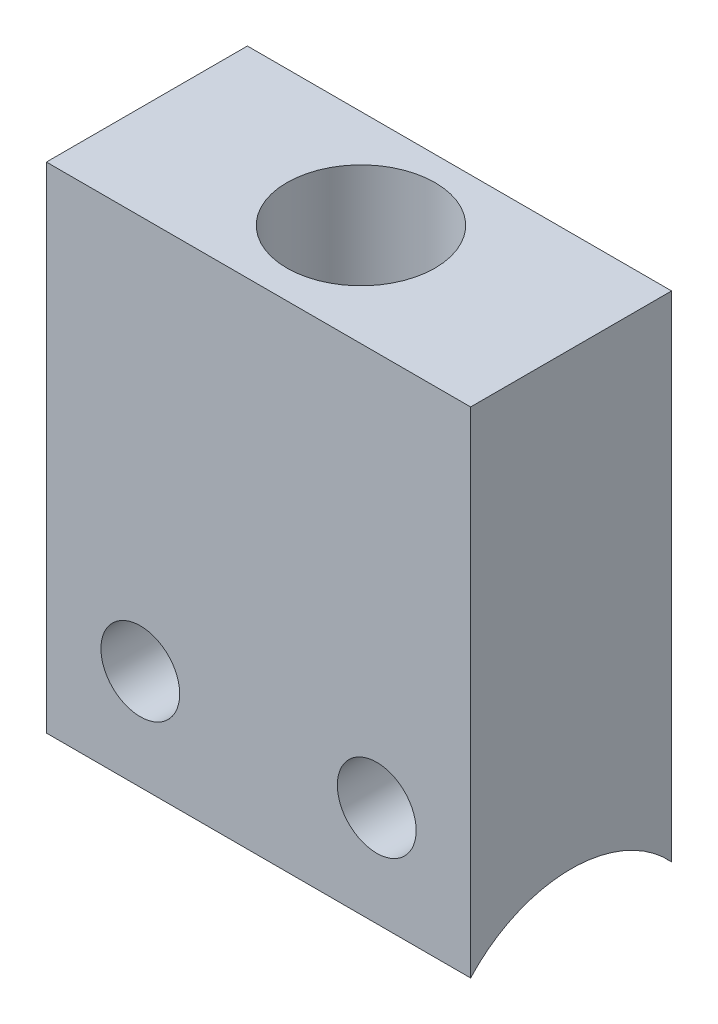
SolidWorks part; units mm, degrees
ref_plane "Front" through (0, 0, 0) normal (0, 0, 1) x (1, 0, 0)
ref_plane "Top" through (0, 0, 0) normal (0, 1, 0) x (1, 0, 0)
ref_plane "Right" through (0, 0, 0) normal (1, 0, 0) x (0, 0, -1)
sketch "Sketch1" plane through (0, 0, 0) normal (0, 0, 1) x (1, 0, 0)
  line L1 (-10.765, 15) -> (10.765, 15)
  line L2 (-10.765, 15) -> (-10.765, -15)
  line L3 (-10.765, -15) -> (10.765, -15)
  line L4 (10.765, 15) -> (10.765, -15)
  line L5 (-10.765, 15) -> (10.765, -15) construction
  line L6 (-10.765, -15) -> (10.765, 15) construction
  point P0 (0, 0)
  dimension "D1" = 21.53
  dimension "D2" = 30
extrude "Boss-Extrude1" add sketch "Sketch1" along normal blind 10.2
sketch "Sketch2" plane through (0, 15, 0) normal (0, 1, 0) x (1, 0, 0)
  line L0 (0, -5.61) -> (0, 5.61) construction
  circle A0 centre (0, -5) radius 3.76
  dimension "D1" = 7.52
extrude "Cut-Extrude1" cut sketch "Sketch2" against normal blind 10
sketch "Sketch3" plane through (10.765, 0, 0) normal (1, 0, 0) x (0, 0, -1)
  line L0 (0, 11.8415) -> (0, -11.8415) construction
  line L2 (-10.2, -10.1003) -> (0, -10.1003)
  line L3 (-10.2, -15) -> (-10.2, 15) construction
  line L4 (-10.2, -15) -> (0, -15) construction
  line L5 (-10.2, -10.1003) -> (0, -10.1003)
  line L6 (-10.2, -10.1003) -> (-10.2, -15)
  line L7 (-10.2, -15) -> (0, -15)
  line L8 (0, -10.1003) -> (0, -15)
  arc A0 (-10.2, -10.1003) -> (0, -10.1003) centre (-5.1, -14.7574) cw
  line M3 (0, -15) -> (0, 15)
  line M5 (-10.2, 15) -> (-10.2, -15)
  line M6 (-10.2, -15) -> (0, -15)
extrude "Cut-Extrude2" cut sketch "Sketch3" against normal up to next contours A0 L2 | L2 M5 M6 M3
sketch "Sketch4" plane through (0, 0, 10.2) normal (0, 0, 1) x (1, 0, 0)
  line L0 (10.765, 15) -> (-10.765, 15) construction
  line L3 (0, -5.61) -> (0, 5.61) construction
  circle A3 centre (-6, -5) radius 2
  circle A4 centre (6, -5) radius 2
  point P2 (0, 0)
  point P8 (0, 0)
  dimension "D1" = 4
  dimension "D3" = 20
  dimension "D2" = 6
extrude "Cut-Extrude3" cut sketch "Sketch4" against normal up to next
